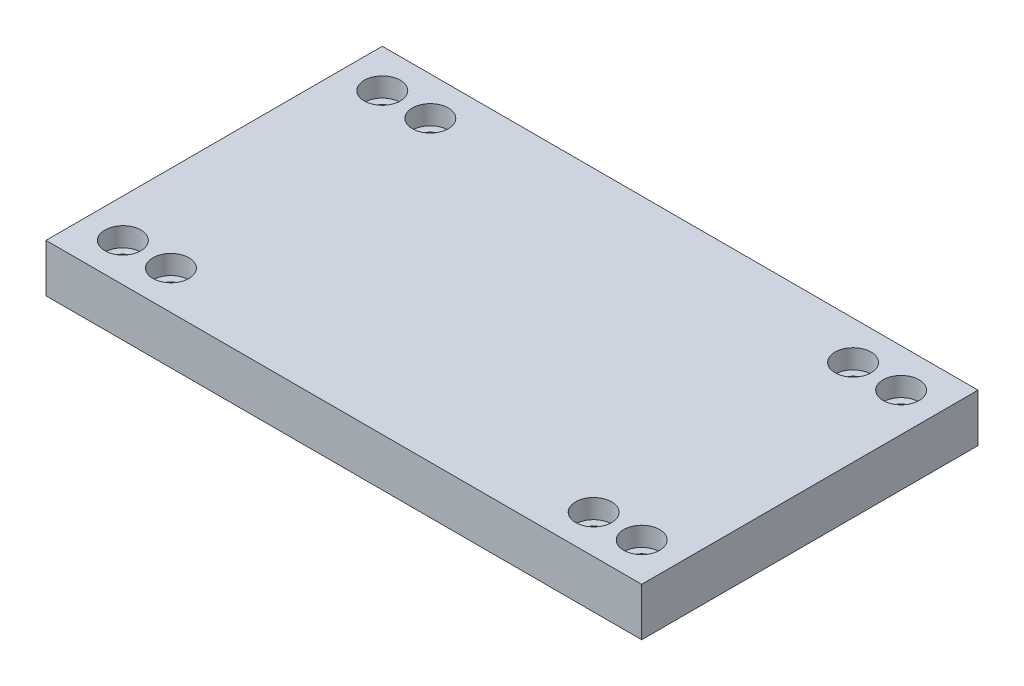
SolidWorks part; units mm, degrees
ref_plane "Front Plane" through (0, 0, 0) normal (0, 0, 1) x (1, 0, 0)
ref_plane "Top Plane" through (0, 0, 0) normal (0, 1, 0) x (1, 0, 0)
ref_plane "Right Plane" through (0, 0, 0) normal (1, 0, 0) x (0, 0, -1)
sketch "Sketch1" plane through (0, 0, 0) normal (0, 1, 0) x (1, 0, 0)
  line L1 (-58.7368, 26.7328) -> (65.2632, 26.7328)
  line L2 (-58.7368, 26.7328) -> (-58.7368, -43.2672)
  line L3 (-58.7368, -43.2672) -> (65.2632, -43.2672)
  line L4 (65.2632, 26.7328) -> (65.2632, -43.2672)
  dimension "D1" = 124
  dimension "D2" = 70
extrude "Boss-Extrude1" add sketch "Sketch1" along normal blind 10 contours L1 L4 L3 L2
sketch "Sketch11" plane through (0, 10, 0) normal (0, 1, 0) x (1, 0, 0)
  line L0 (-58.7368, 26.7328) -> (-58.7368, -43.2672) construction
  line L1 (-58.7368, 26.7328) -> (65.2632, 26.7328) construction
  line L2 (-58.7368, -43.2672) -> (65.2632, -43.2672) construction
  line L3 (65.2632, 26.7328) -> (65.2632, -43.2672) construction
  circle A0 centre (-50.7368, 18.7328) radius 2.15
  circle A2 centre (-40.7368, 18.7328) radius 2.15
  circle A4 centre (-50.7368, -35.2672) radius 2.15
  circle A5 centre (-40.7368, -35.2672) radius 2.15
  circle A6 centre (47.2632, 18.7328) radius 2.15
  circle A7 centre (57.2632, 18.7328) radius 2.15
  circle A8 centre (47.2632, -35.2672) radius 2.15
  circle A9 centre (57.2632, -35.2672) radius 2.15
  point P24 (0, 0)
  dimension "D1" = 8
  dimension "D3" = 10
  dimension "D5" = 10
  dimension "D2" = 8
  dimension "D4" = 0
  dimension "D6" = 0
  dimension "D7" = 8
  dimension "D8" = 8
  dimension "D9" = 10
  dimension "D10" = 8
  dimension "D11" = 8
  dimension "D12" = 8
  dimension "D13" = 8
  dimension "D14" = 10
  dimension "D15" = 8
extrude "Cut-Extrude4" cut sketch "Sketch11" against normal through all
sketch "Sketch17" plane through (0, 10, 0) normal (0, 1, 0) x (1, 0, 0)
  circle A0 centre (-50.7368, 18.7328) radius 3.75
  circle A1 centre (-40.7368, 18.7328) radius 3.75
  circle A2 centre (47.2632, 18.7328) radius 3.75
  circle A3 centre (57.2632, 18.7328) radius 3.75
  circle A4 centre (57.2632, -35.2672) radius 3.75
  circle A5 centre (47.2632, -35.2672) radius 3.75
  circle A6 centre (-40.7368, -35.2672) radius 3.75
  circle A7 centre (-50.7368, -35.2672) radius 3.75
extrude "Cut-Extrude5" cut sketch "Sketch17" against normal blind 4
